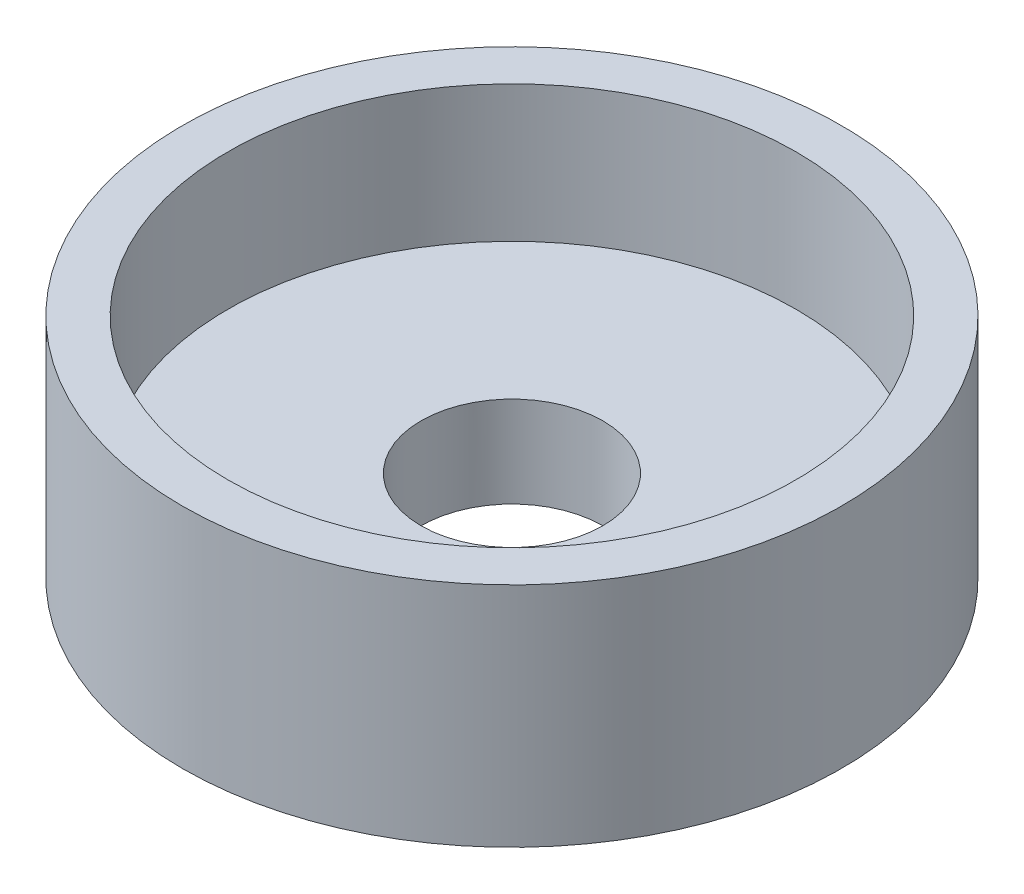
SolidWorks part; units mm, degrees
ref_plane "Спереди" through (0, 0, 0) normal (0, 0, 1) x (1, 0, 0)
ref_plane "Сверху" through (0, 0, 0) normal (0, 1, 0) x (1, 0, 0)
ref_plane "Справа" through (0, 0, 0) normal (1, 0, 0) x (0, 0, -1)
sketch "Sketch1" plane through (0, 0, 0) normal (0, 1, 0) x (1, 0, 0)
  circle A0 centre (0, 0) radius 14.5
  dimension "D1" = 29
extrude "Boss-Extrude1" add sketch "Sketch1" along normal blind 10
sketch "Sketch2" plane through (0, 10, 0) normal (0, 1, 0) x (1, 0, 0)
  circle A0 centre (0, 0) radius 12.5
  dimension "D1" = 25
extrude "Cut-Extrude1" cut sketch "Sketch2" against normal blind 6
sketch "Sketch3" plane through (0, 0, 0) normal (0, -1, 0) x (1, 0, 0)
  circle A0 centre (0, 0) radius 4
  dimension "D1" = 8
extrude "Cut-Extrude2" cut sketch "Sketch3" against normal through all
